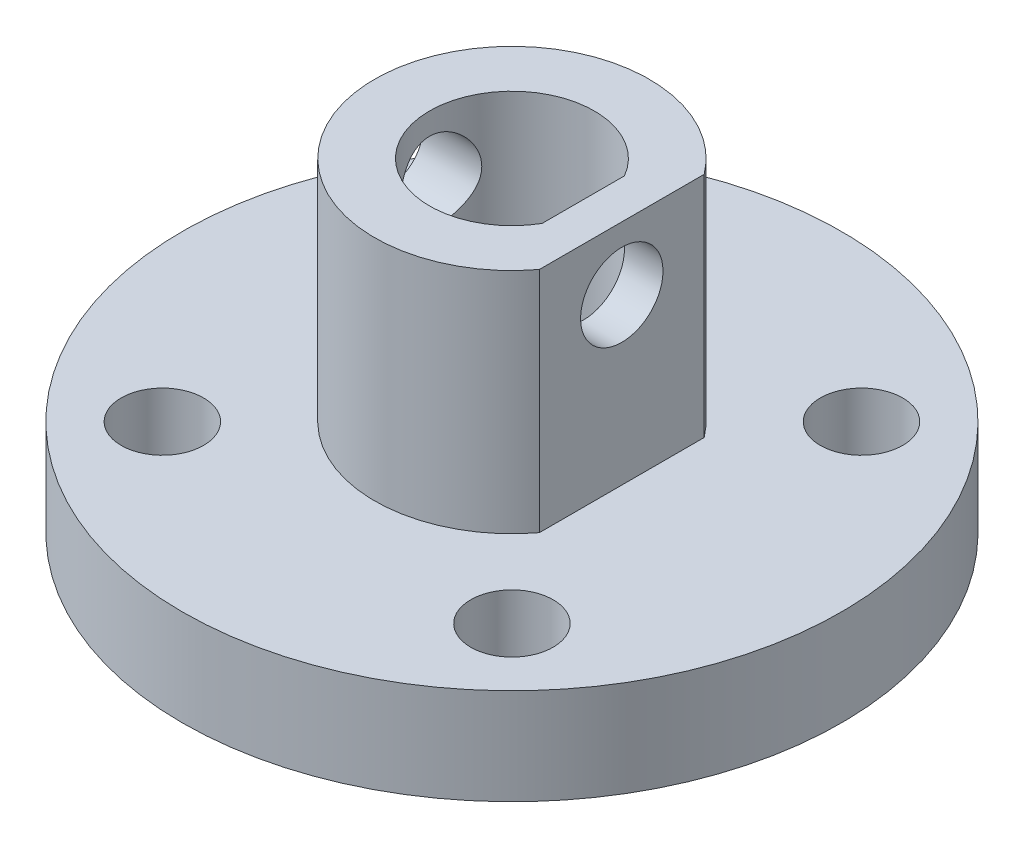
SolidWorks part; units mm, degrees
material "6061 Alloy"
ref_plane "前视基准面" through (0, 0, 0) normal (0, 0, 1) x (1, 0, 0)
ref_plane "上视基准面" through (0, 0, 0) normal (0, 1, 0) x (1, 0, 0)
ref_plane "右视基准面" through (0, 0, 0) normal (1, 0, 0) x (0, 0, -1)
sketch "Sketch1" plane through (0, 0, 0) normal (0, 1, 0) x (1, 0, 0)
  line L0 (0, 0) -> (6.364, 6.364)
  line L1 (2.5981, 1.5) -> (2.5981, -1.5)
  circle A0 centre (0, 0) radius 12
  circle A1 centre (6.364, 6.364) radius 1.5
  circle A2 centre (6.364, -6.364) radius 1.5
  circle A3 centre (-6.364, -6.364) radius 1.5
  circle A4 centre (-6.364, 6.364) radius 1.5
  circle A5 centre (0, 0) radius 3
  point P14 (0, 0)
  dimension "D1" = 24
  dimension "D3" = 3
  dimension "D5" = 6
  dimension "D2" = 9
  dimension "D6" = 3
  dimension "D4" = 4
extrude "Boss-Extrude1" add sketch "Sketch1" along normal blind 3.5
sketch "Sketch2" plane through (0, 3.5, 0) normal (0, 1, 0) x (1, 0, 0)
  line L0 (2.5981, 1.5) -> (2.5981, -1.5)
  line L1 (4, 3) -> (4, -3)
  circle A0 centre (0, 0) radius 5
  circle A1 centre (0, 0) radius 3
  dimension "D1" = 10
  dimension "D2" = 6
  dimension "D3" = 3
  dimension "D4" = 4
extrude "Boss-Extrude2" add sketch "Sketch2" along normal blind 8.3 contours L1 A0 A1 | L0 A1
sketch "Sketch3" plane through (4, 0, 0) normal (1, 0, 0) x (0, 0, -1)
  line L2 (3, 3.5) -> (-3, 3.5) construction
  line L3 (3, 11.8) -> (-3, 11.8) construction
  circle A0 centre (0, 9.5) radius 1.5
  point P7 (0, 11.8)
  dimension "D1" = 3
  dimension "D2" = 6
extrude "Cut-Extrude1" cut sketch "Sketch3" against normal blind 19
